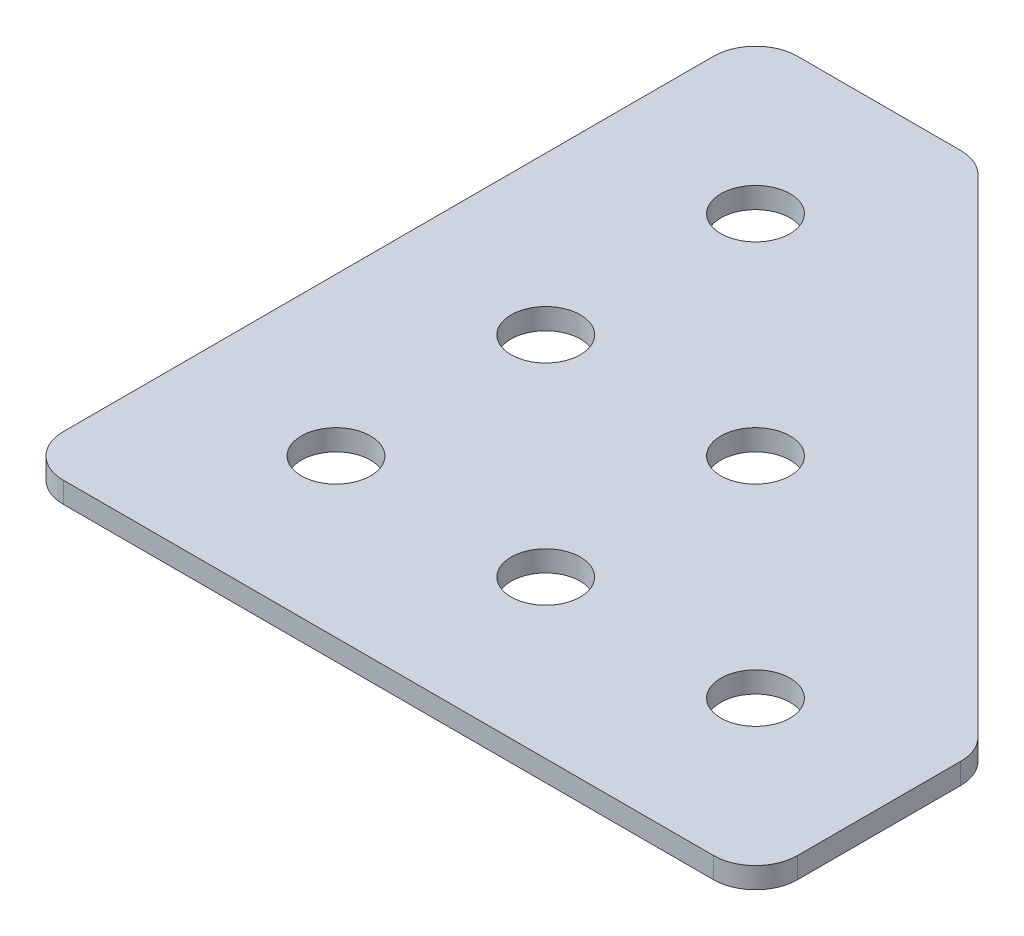
SolidWorks part; units mm, degrees
ref_plane "Front Plane" through (0, 0, 0) normal (0, 0, 1) x (1, 0, 0)
ref_plane "Top Plane" through (0, 0, 0) normal (0, 1, 0) x (1, 0, 0)
ref_plane "Right Plane" through (0, 0, 0) normal (1, 0, 0) x (0, 0, -1)
sketch "Sketch1" plane through (0, 0, 0) normal (0, 1, 0) x (1, 0, 0)
  line L0 (0, 2) -> (0, 33)
  line L1 (11.1924, 34.4142) -> (34.4142, 11.1924)
  line L2 (33, 0) -> (2, 0)
  line L3 (2, 35) -> (9.7782, 35)
  line L4 (35, 9.7782) -> (35, 2)
  arc A0 (33, 0) -> (35, 2) centre (33, 2) ccw
  arc A1 (35, 9.7782) -> (34.4142, 11.1924) centre (33, 9.7782) ccw
  arc A2 (0, 2) -> (2, 0) centre (2, 2) ccw
  circle A3 centre (7.5, 7.5) radius 1.65
  circle A4 centre (7.5, 27.5) radius 1.65
  circle A5 centre (17.5, 7.5) radius 1.65
  circle A6 centre (27.5, 7.5) radius 1.65
  circle A7 centre (7.5, 17.5) radius 1.65
  circle A8 centre (17.5, 17.5) radius 1.65
  arc A9 (9.7782, 35) -> (11.1924, 34.4142) centre (9.7782, 33) cw
  arc A10 (0, 33) -> (2, 35) centre (2, 33) cw
  point P10 (0, 0)
  dimension "D2" = 7.5
  dimension "D3" = 2
  dimension "D5" = 3.3
  dimension "D6" = 3.3
  dimension "D7" = 7.5
  dimension "D21" = 2
  dimension "D22" = 3.3
  dimension "D23" = 3.3
  dimension "D24" = 3.3
  dimension "D25" = 3.3
  dimension "D4" = 7.5
  dimension "D8" = 7.5
  dimension "D9" = 7.5
  dimension "D10" = 7.5
  dimension "D11" = 7.5
  dimension "D12" = 7.5
  dimension "D13" = 10
  dimension "D14" = 10
  dimension "D15" = 10
  dimension "D16" = 10
  dimension "D17" = 10
  dimension "D18" = 10
  dimension "D19" = 7.5
  dimension "D20" = 7.5
extrude "Boss-Extrude1" add sketch "Sketch1" along normal blind 1
